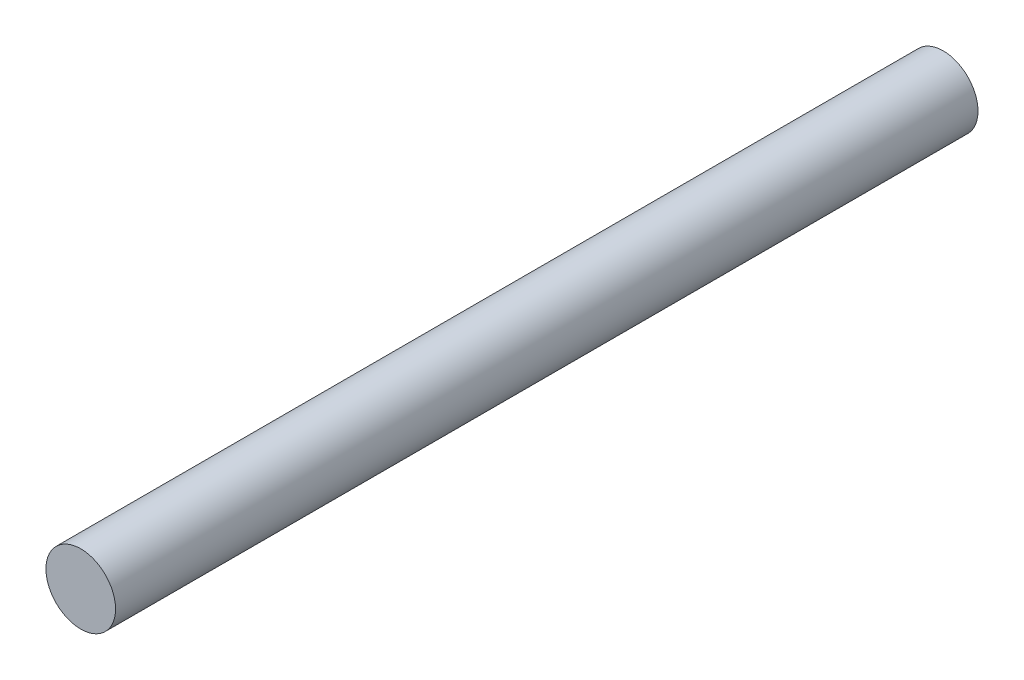
SolidWorks part; units mm, degrees
material "6061 Alloy"
ref_plane "Front Plane" through (0, 0, 0) normal (0, 0, 1) x (1, 0, 0)
ref_plane "Top Plane" through (0, 0, 0) normal (0, 1, 0) x (1, 0, 0)
ref_plane "Right Plane" through (0, 0, 0) normal (1, 0, 0) x (0, 0, -1)
sketch "Sketch1" plane through (0, 0, 0) normal (0, 0, 1) x (1, 0, 0)
  circle A0 centre (0, 0) radius 11.3
extrude "Boss-Extrude1" add sketch "Sketch1" along normal blind 280
